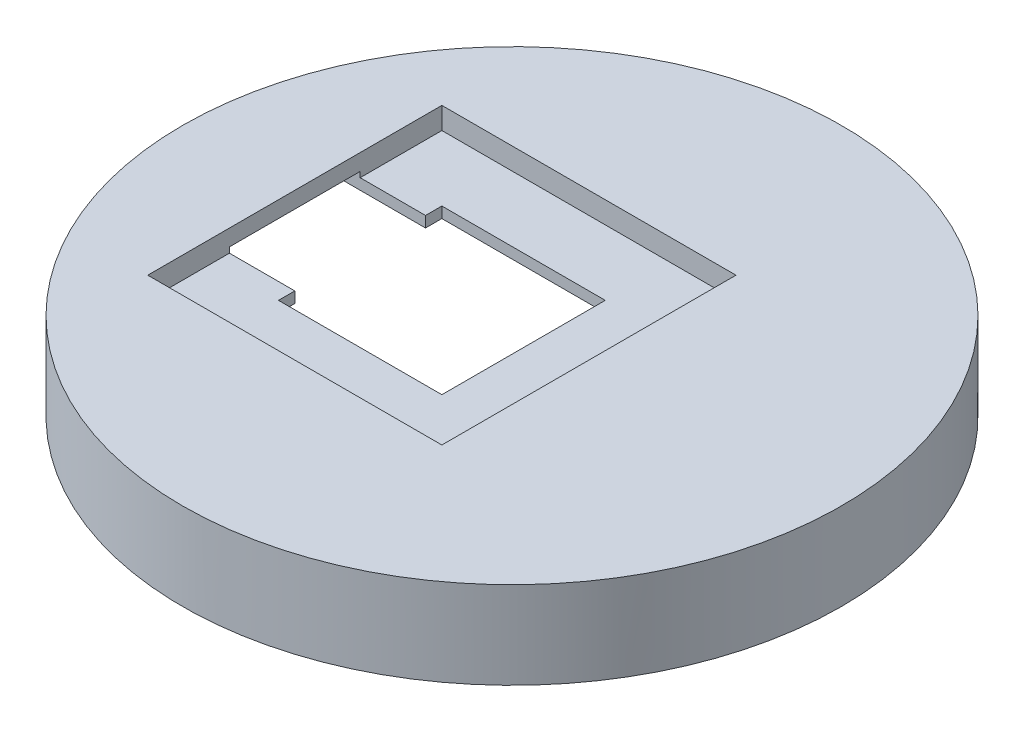
SolidWorks part; units mm, degrees
ref_plane "Front Plane" through (0, 0, 0) normal (0, 0, 1) x (1, 0, 0)
ref_plane "Top Plane" through (0, 0, 0) normal (0, 1, 0) x (1, 0, 0)
ref_plane "Right Plane" through (0, 0, 0) normal (1, 0, 0) x (0, 0, -1)
sketch "base" plane through (0, 0, 0) normal (0, 1, 0) x (1, 0, 0)
  circle A0 centre (0, 0) radius 30.25
extrude "extrusao_base" add sketch "base" along normal blind 8
sketch "corte_base" plane through (0, 0, 0) normal (0, 1, 0) x (1, 0, 0)
  circle A0 centre (0, 0) radius 28.75
extrude "extrusao_corte_base" cut sketch "corte_base" along normal blind 5
sketch "mid_line" plane through (0, 0, 0) normal (0, 1, 0) x (1, 0, 0)
  line L0 (-64.917, 0) -> (69.5719, 0) construction
ref_plane "Plane2" through (0, 0, 0) normal (0, 0, 1) x (1, 0, 0)
sketch "usb" plane through (0, 0, 0) normal (0, 1, 0) x (1, 0, 0)
  line L0 (-73.9689, 0) -> (73.9689, 0) construction
  line L1 (-142.5267, 6) -> (0, 6)
  line L2 (-142.5267, 6) -> (-142.5267, -6)
  line L3 (-142.5267, -6) -> (0, -6)
  line L4 (0, 6) -> (0, -6)
  line L5 (-142.5267, 6) -> (0, -6) construction
  line L6 (-142.5267, -6) -> (0, 6) construction
  point P0 (-71.2633, 0)
extrude "corte_usb" cut sketch "usb" along normal blind 6.5
sketch "prisma" plane through (0, 8, 0) normal (0, 1, 0) x (1, 0, 0)
  line L0 (-64.917, 0) -> (69.5719, 0) construction
  line L1 (-19.9385, 13.5) -> (7.0615, 13.5)
  line L2 (-19.9385, 13.5) -> (-19.9385, -13.5)
  line L3 (-19.9385, -13.5) -> (7.0615, -13.5)
  line L4 (7.0615, 13.5) -> (7.0615, -13.5)
  line L5 (-19.9385, 13.5) -> (7.0615, -13.5) construction
  line L6 (-19.9385, -13.5) -> (7.0615, 13.5) construction
  point P0 (-6.4385, 0)
sketch "prisma2"
  line L4 (-13.9385, 7.5) -> (1.0615, 7.5)
  line L5 (-13.9385, 7.5) -> (-13.9385, -7.5)
  line L6 (-13.9385, -7.5) -> (1.0615, -7.5)
  line L7 (1.0615, 7.5) -> (1.0615, -7.5)
  line L8 (-13.9385, 7.5) -> (1.0615, -7.5) construction
  line L9 (-13.9385, -7.5) -> (1.0615, 7.5) construction
  point P6 (-6.4385, 0)
other "AlignGroup1"
other "AlignGroup2"
extrude "corte_prisma" cut sketch "prisma2" along normal through all both and the other way through all
extrude "corte_encaixe_prisma" cut sketch "prisma" against normal blind 2
